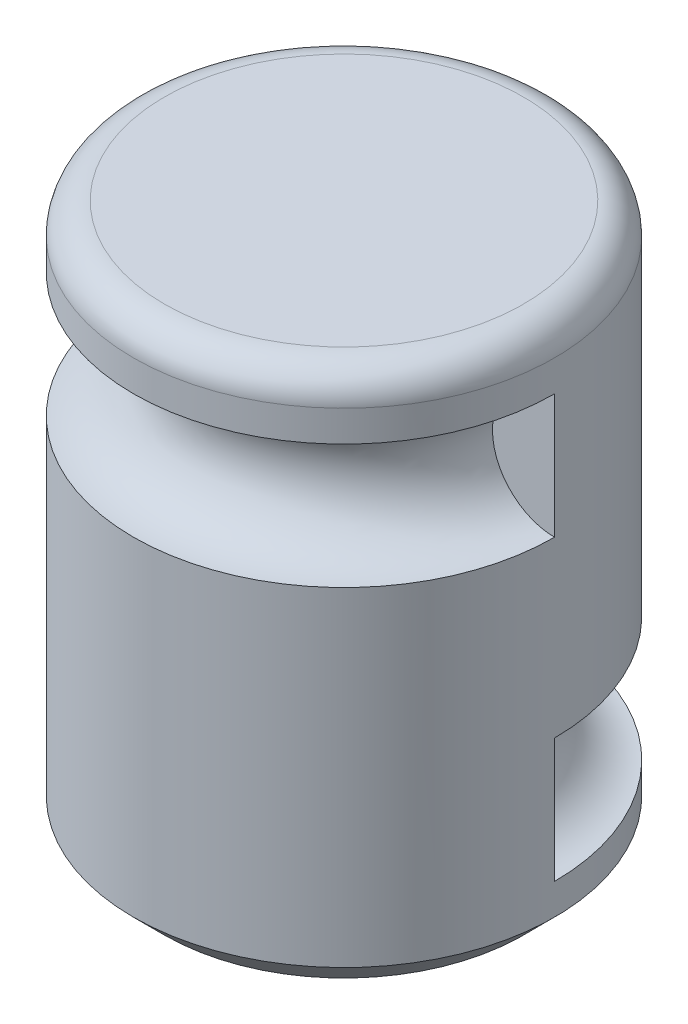
SolidWorks part; units mm, degrees
material "Cast Alloy Steel"
ref_plane "Front Plane" through (0, 0, 0) normal (0, 0, 1) x (1, 0, 0)
ref_plane "Top Plane" through (0, 0, 0) normal (0, 1, 0) x (1, 0, 0)
ref_plane "Right Plane" through (0, 0, 0) normal (1, 0, 0) x (0, 0, -1)
sketch "Sketch1" plane through (0, 0, 0) normal (0, 1, 0) x (1, 0, 0)
  circle A0 centre (0, 0) radius 33.9054
extrude "Boss-Extrude1" add sketch "Sketch1" along normal blind 88
sketch "Sketch2" plane through (0, 0, 0) normal (0, 0, 1) x (1, 0, 0)
  line L0 (33.9054, 0) -> (33.9054, 88) construction
  line L1 (-33.9054, 88) -> (-33.9054, 0) construction
  line L2 (-33.9054, 0) -> (33.9054, 0) construction
  line L3 (33.9054, 88) -> (-33.9054, 88) construction
  line L4 (0, 39.0827) -> (0, -11.1685) construction
  circle A0 centre (33.9054, 68) radius 10
  circle A1 centre (-33.9054, 20) radius 10
  dimension "D1" = 20
  dimension "D2" = 20
  dimension "D3" = 20
  dimension "D4" = 20
revolve "Cut-Revolve1" cut sketch "Sketch2" angle 180 about L4
fillet "Fillet1" radius 5 1 edges at (0, 88, 33.9054)
chamfer "Chamfer1" distance 5 angle 45 1 edges at (0, 0, 33.9054)
